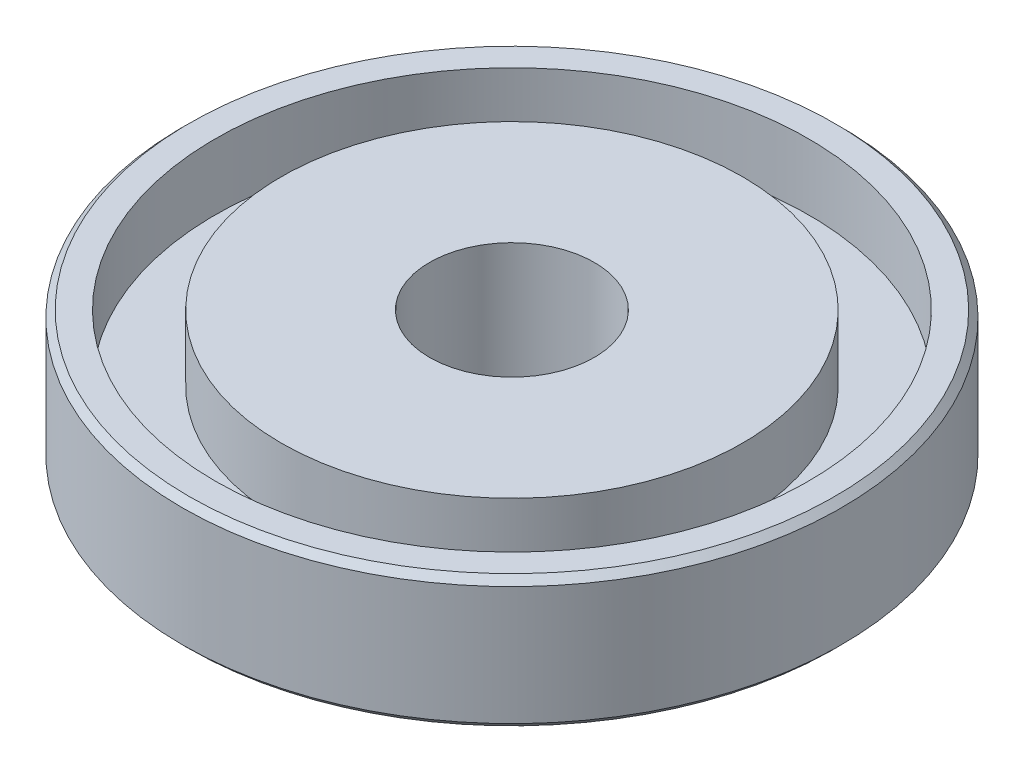
SolidWorks part; units mm, degrees
ref_plane "前视基准面" through (0, 0, 0) normal (0, 0, 1) x (1, 0, 0)
ref_plane "上视基准面" through (0, 0, 0) normal (0, 1, 0) x (1, 0, 0)
ref_plane "右视基准面" through (0, 0, 0) normal (1, 0, 0) x (0, 0, -1)
sketch "草图1" plane through (0, 0, 0) normal (0, 1, 0) x (1, 0, 0)
  circle A0 centre (0, 0) radius 50
extrude "凸台-拉伸1" add sketch "草图1" along normal blind 20
ref_plane "基准面1" through (0, 20, 0) normal (0, 1, 0) x (1, 0, 0)
sketch "草图2" plane through (0, 20, 0) normal (0, 1, 0) x (1, 0, 0)
  circle A0 centre (0, 0) radius 45
  circle A1 centre (0, 0) radius 35
extrude "切除-拉伸1" cut sketch "草图2" against normal blind 10
sketch "草图3" plane through (0, 0, 0) normal (0, 1, 0) x (1, 0, 0)
  circle A0 centre (0, 0) radius 12.5
extrude "切除-拉伸2" cut sketch "草图3" along normal through all
chamfer "倒角1" distance 1 angle 45 2 edges at (0, 0, 50) (0, 20, 50)
